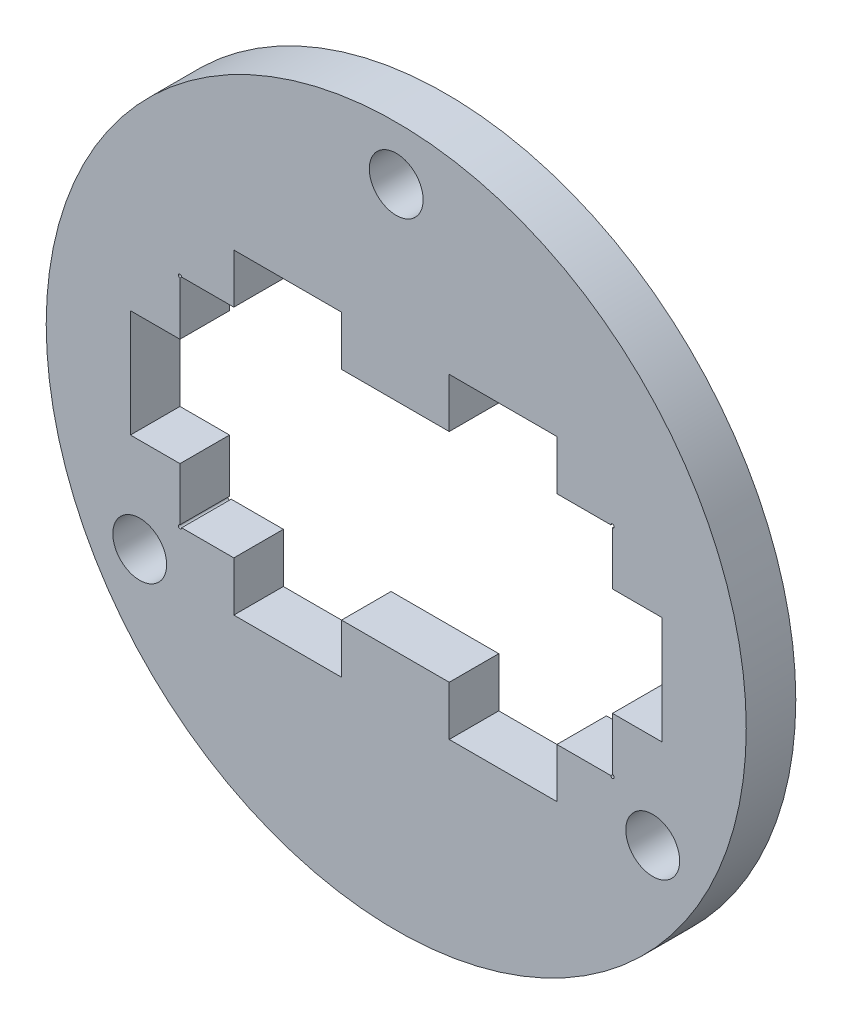
SolidWorks part; units mm, degrees
ref_plane "Front Plane" through (0, 0, 0) normal (0, 0, 1) x (1, 0, 0)
ref_plane "Top Plane" through (0, 0, 0) normal (0, 1, 0) x (1, 0, 0)
ref_plane "Right Plane" through (0, 0, 0) normal (1, 0, 0) x (0, 0, -1)
sketch "Sketch1" plane through (0, 0, 0) normal (0, 0, 1) x (1, 0, 0)
  line L1 (-25.3016, -12.8) -> (25.3016, -12.8)
  line L2 (-25.5, -12.6016) -> (-25.5, 12.6016)
  line L3 (-25.3016, 12.8) -> (25.3016, 12.8)
  line L4 (25.5, -12.6016) -> (25.5, 12.6016)
  line L5 (-25.5, -12.8) -> (25.5, 12.8) construction
  line L6 (-25.5, 12.8) -> (25.5, -12.8) construction
  circle A0 centre (0, 34.925) radius 3.175
  circle A1 centre (0, 34.925) radius 4.7625 construction
  circle A2 centre (30.2459, -17.4625) radius 6.35 construction
  circle A3 centre (30.2459, -17.4625) radius 4.7625 construction
  circle A4 centre (30.2459, -17.4625) radius 3.175
  circle A5 centre (-30.2459, -17.4625) radius 6.35 construction
  circle A6 centre (0, 0) radius 41.275
  circle A7 centre (0, 34.925) radius 6.35 construction
  circle A8 centre (-30.2459, -17.4625) radius 4.7625 construction
  circle A9 centre (-30.2459, -17.4625) radius 3.175
  arc A10 (25.5, 12.6016) -> (25.3016, 12.8) centre (25.5, 12.8) ccw
  arc A11 (25.3016, -12.8) -> (25.5, -12.6016) centre (25.5, -12.8) ccw
  arc A12 (-25.3016, 12.8) -> (-25.5, 12.6016) centre (-25.5, 12.8) ccw
  arc A13 (-25.5, -12.6016) -> (-25.3016, -12.8) centre (-25.5, -12.8) ccw
  point P0 (0, 0)
  point P25 (0, 0)
  dimension "D3" = 1.5875
  dimension "D6" = 6.35
  dimension "D1" = 82.55
  dimension "D2" = 34.925
  dimension "D4" = 51
  dimension "D5" = 25.6
extrude "Boss-Extrude1" add sketch "Sketch1" along normal blind 5.842
sketch "Sketch7" plane through (0, 0, 0) normal (0, 0, -1) x (-1, 0, 0)
  circle A0 centre (0, 0) radius 41.275
  circle A1 centre (0, 0) radius 39.4875
  dimension "D1" = 78.975
extrude "Cut-Extrude3" cut sketch "Sketch7" against normal through all
sketch "Sketch8" plane through (0, 0, 0) normal (0, 0, -1) x (-1, 0, 0)
  line L0 (25.3016, 12.8) -> (-25.3016, 12.8) construction
  line L3 (0, 0) -> (39.4875, 0) construction
  line L4 (-25.5, -12.6016) -> (-25.5, 12.6016) construction
  line L5 (-31.342, -6.35) -> (-25.5, -6.35)
  line L6 (-31.342, -6.35) -> (-31.342, 6.35)
  line L7 (-18.95, 12.8) -> (-6.25, 12.8)
  line L8 (-18.95, 12.8) -> (-18.95, 18.642)
  line L9 (-18.95, 18.642) -> (-6.25, 18.642)
  line L10 (-6.25, 12.8) -> (-6.25, 18.642)
  line L11 (-18.95, 12.8) -> (-6.25, 18.642) construction
  line L12 (-18.95, 18.642) -> (-6.25, 12.8) construction
  line L13 (19.15, 18.642) -> (6.45, 12.8) construction
  line L14 (19.15, 12.8) -> (6.45, 18.642) construction
  line L15 (6.45, 12.8) -> (6.45, 18.642)
  line L16 (19.15, 18.642) -> (6.45, 18.642)
  line L17 (19.15, 12.8) -> (19.15, 18.642)
  line L18 (19.15, 12.8) -> (6.45, 12.8)
  line L19 (0, 0) -> (-39.4875, 0) construction
  line L20 (19.15, -12.8) -> (6.45, -18.642) construction
  line L21 (19.15, -18.642) -> (6.45, -12.8) construction
  line L22 (-18.95, -18.642) -> (-6.25, -12.8) construction
  line L23 (-18.95, -12.8) -> (-6.25, -18.642) construction
  line L24 (19.15, -12.8) -> (6.45, -12.8)
  line L25 (19.15, -12.8) -> (19.15, -18.642)
  line L26 (19.15, -18.642) -> (6.45, -18.642)
  line L27 (6.45, -12.8) -> (6.45, -18.642)
  line L28 (-6.25, -12.8) -> (-6.25, -18.642)
  line L29 (-18.95, -18.642) -> (-6.25, -18.642)
  line L30 (-18.95, -12.8) -> (-18.95, -18.642)
  line L31 (-18.95, -12.8) -> (-6.25, -12.8)
  line L32 (-31.342, 6.35) -> (-25.5, 6.35)
  line L33 (-25.5, -6.35) -> (-25.5, 6.35)
  line L34 (-31.342, -6.35) -> (-25.5, 6.35) construction
  line L35 (-31.342, 6.35) -> (-25.5, -6.35) construction
  line L36 (0, 12.8) -> (0, -12.8) construction
  line L37 (25.3016, -12.8) -> (-25.3016, -12.8) construction
  line L38 (31.342, 6.35) -> (25.5, -6.35) construction
  line L39 (31.342, -6.35) -> (25.5, 6.35) construction
  line L40 (25.5, -6.35) -> (25.5, 6.35)
  line L41 (31.342, 6.35) -> (25.5, 6.35)
  line L42 (31.342, -6.35) -> (31.342, 6.35)
  line L43 (31.342, -6.35) -> (25.5, -6.35)
  circle A0 centre (0, 0) radius 39.4875 construction
  point P12 (-12.6, 15.721)
  point P19 (12.8, 15.821)
  point P25 (12.8, -15.821)
  point P26 (-12.6, -15.721)
  point P27 (-28.421, 0)
  point P44 (28.421, 0)
  dimension "D1" = 12.7
  dimension "D2" = 5.842
  dimension "D3" = 5.842
  dimension "D4" = 12.7
extrude "Cut-Extrude4" cut sketch "Sketch8" against normal through all
sketch "Sketch9" plane through (0, 0, 0) normal (0, 0, -1) x (-1, 0, 0)
  circle A0 centre (0, 0) radius 39.4875
  circle A1 centre (0, 0) radius 41.275
  dimension "D1" = 82.55
extrude "Boss-Extrude2" add sketch "Sketch9" against normal blind 5.842
